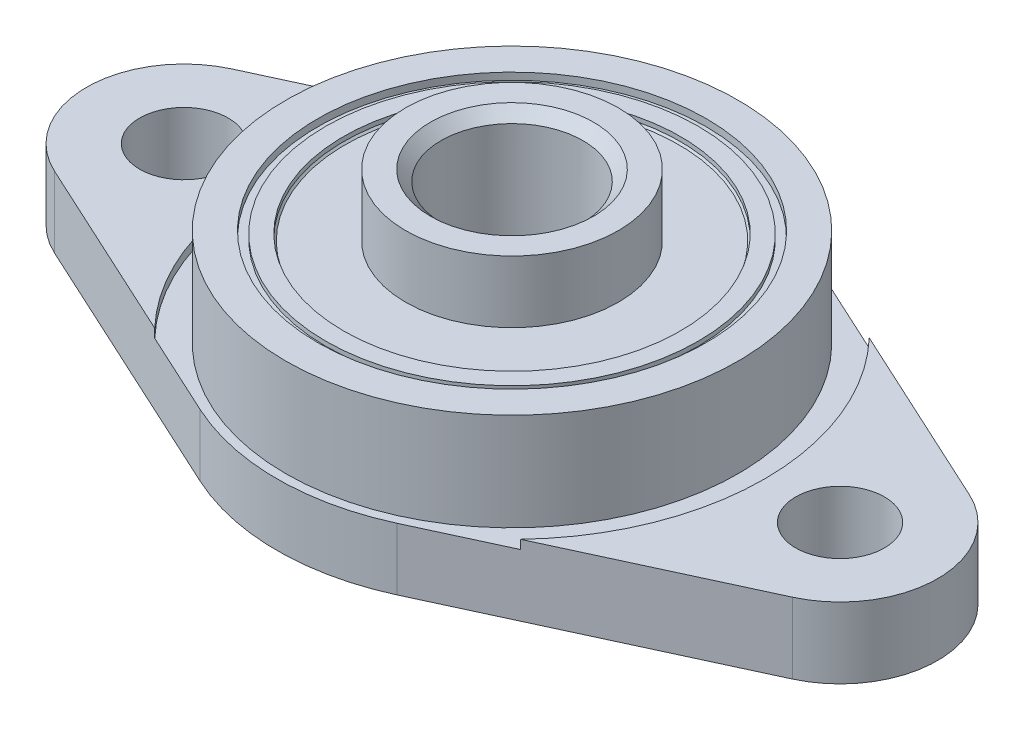
SolidWorks part; units mm, degrees
ref_plane "Front Plane" through (0, 0, 0) normal (0, 0, 1) x (1, 0, 0)
ref_plane "Top Plane" through (0, 0, 0) normal (0, 1, 0) x (1, 0, 0)
ref_plane "Right Plane" through (0, 0, 0) normal (1, 0, 0) x (0, 0, -1)
sketch "Sketch2" plane through (0, 0, 0) normal (0, 1, 0) x (1, 0, 0)
  line L0 (0, 15.7574) -> (0, -15.7574) construction
  line L1 (-5.5507, 12.0313) -> (-20.8041, 4.9941)
  line L2 (-37.1587, 0) -> (38.3179, 0) construction
  line L3 (5.5507, 12.0313) -> (20.8041, 4.9941)
  line L4 (5.5507, -12.0313) -> (20.8041, -4.9941)
  line L5 (-5.5507, -12.0313) -> (-20.8041, -4.9941)
  circle A0 centre (-18.5, 0) radius 2.5
  arc A1 (-20.8041, 4.9941) -> (-20.8041, -4.9941) centre (-18.5, 0) ccw
  arc A2 (5.5507, 12.0313) -> (-5.5507, 12.0313) centre (0, 0) ccw
  circle A3 centre (18.5, 0) radius 2.5
  arc A4 (20.8041, 4.9941) -> (20.8041, -4.9941) centre (18.5, 0) cw
  arc A5 (-5.5507, -12.0313) -> (5.5507, -12.0313) centre (0, 0) ccw
  dimension "D1" = 2.5
  dimension "D2" = 5.5
  dimension "D3" = 26.5
  dimension "D4" = 18.5
extrude "Boss-Extrude1" add sketch "Sketch2" along normal blind 4
sketch "Sketch3" plane through (0, 4, 0) normal (0, 1, 0) x (1, 0, 0)
  circle A0 centre (0, 0) radius 14.25
  dimension "D1" = 14.25
extrude "Cut-Extrude1" cut sketch "Sketch3" against normal blind 0.5
sketch "Sketch4" plane through (0, 3.5, 0) normal (0, 1, 0) x (1, 0, 0)
  circle A0 centre (0, 0) radius 12.75
  dimension "D1" = 12.75
extrude "Boss-Extrude2" add sketch "Sketch4" along normal blind 5.5
sketch "Sketch5" plane through (0, 0, 0) normal (0, -1, 0) x (1, 0, 0)
  line L8 (4.8385, -10.4877) -> (20.0919, -3.4505)
  line L9 (20.0919, 3.4505) -> (4.8385, 10.4877)
  line L10 (-4.8385, 10.4877) -> (-20.0919, 3.4505)
  line L11 (-20.0919, -3.4505) -> (-4.8385, -10.4877)
  line L12 (4.8385, -10.4877) -> (16.4814, -5.1162)
  line L13 (16.4814, 5.1162) -> (4.8385, 10.4877)
  line L14 (-4.8385, 10.4877) -> (-16.4814, 5.1162)
  line L15 (-16.4814, -5.1162) -> (-4.8385, -10.4877)
  arc A4 (-16.4814, -5.1162) -> (-16.4814, 5.1162) centre (-18.5, 0) ccw
  arc A5 (16.4814, 5.1162) -> (16.4814, -5.1162) centre (18.5, 0) ccw
  arc A8 (-4.8385, -10.4877) -> (4.8385, -10.4877) centre (0, 0) ccw
  arc A9 (20.0919, -3.4505) -> (20.0919, 3.4505) centre (18.5, 0) ccw
  arc A10 (4.8385, 10.4877) -> (-4.8385, 10.4877) centre (0, 0) ccw
  arc A11 (-20.0919, 3.4505) -> (-20.0919, -3.4505) centre (-18.5, 0) ccw
  arc A12 (-4.8385, -10.4877) -> (4.8385, -10.4877) centre (0, 0) ccw
  arc A14 (4.8385, 10.4877) -> (-4.8385, 10.4877) centre (0, 0) ccw
  dimension "5.5" = 5.5
  dimension "D1" = 1.7
extrude "Cut-Extrude2" cut sketch "Sketch5" against normal blind 0.5
sketch "Sketch6" plane through (0, 9, 0) normal (0, 1, 0) x (1, 0, 0)
  circle A0 centre (0, 0) radius 10.95
  dimension "D1" = 21.9
extrude "Cut-Extrude3" cut sketch "Sketch6" against normal blind 0.4
sketch "Sketch7" plane through (0, 8.6, 0) normal (0, 1, 0) x (1, 0, 0)
  circle A0 centre (0, 0) radius 10.5
  dimension "D1" = 10.5
extrude "Boss-Extrude3" add sketch "Sketch7" along normal blind 0.25
sketch "Sketch8" plane through (0, 8.85, 0) normal (0, 1, 0) x (1, 0, 0)
  circle A0 centre (0, 0) radius 9.5
  dimension "D1" = 19
extrude "Cut-Extrude4" cut sketch "Sketch8" against normal blind 0.35
sketch "Sketch9" plane through (0, 0.5, 0) normal (0, -1, 0) x (1, 0, 0)
  circle A0 centre (0, 0) radius 10.5
  dimension "D1" = 21
extrude "Boss-Extrude4" add sketch "Sketch9" along normal blind 0.25
sketch "Sketch10" plane through (0, 0.25, 0) normal (0, -1, 0) x (1, 0, 0)
  circle A0 centre (0, 0) radius 9.5
  dimension "D1" = 19
extrude "Cut-Extrude5" cut sketch "Sketch10" against normal blind 0.35
sketch "Sketch11" plane through (0, 0.6, 0) normal (0, -1, 0) x (1, 0, 0)
  circle A0 centre (0, 0) radius 6
  dimension "D1" = 12
extrude "Boss-Extrude5" add sketch "Sketch11" along normal blind 0.35
sketch "Sketch12" plane through (0, 8.5, 0) normal (0, 1, 0) x (1, 0, 0)
  circle A0 centre (0, 0) radius 6
  dimension "D1" = 12
extrude "Boss-Extrude6" add sketch "Sketch12" along normal blind 3.5
sketch "Sketch13" plane through (0, 12, 0) normal (0, 1, 0) x (1, 0, 0)
  circle A0 centre (0, 0) radius 4
  dimension "D1" = 4
extrude "Cut-Extrude6" cut sketch "Sketch13" against normal through all both and the other way through all
chamfer "Chamfer1" distance 0.6 angle 45 1 edges at (0, 12, 4)
chamfer "Chamfer2" distance 0.6 angle 45 1 edges at (0, 0.25, -4)
chamfer "Chamfer3" distance 0.1 angle 45 2 edges at (0, 0.6, -9.5) (0, 8.5, 9.5)
